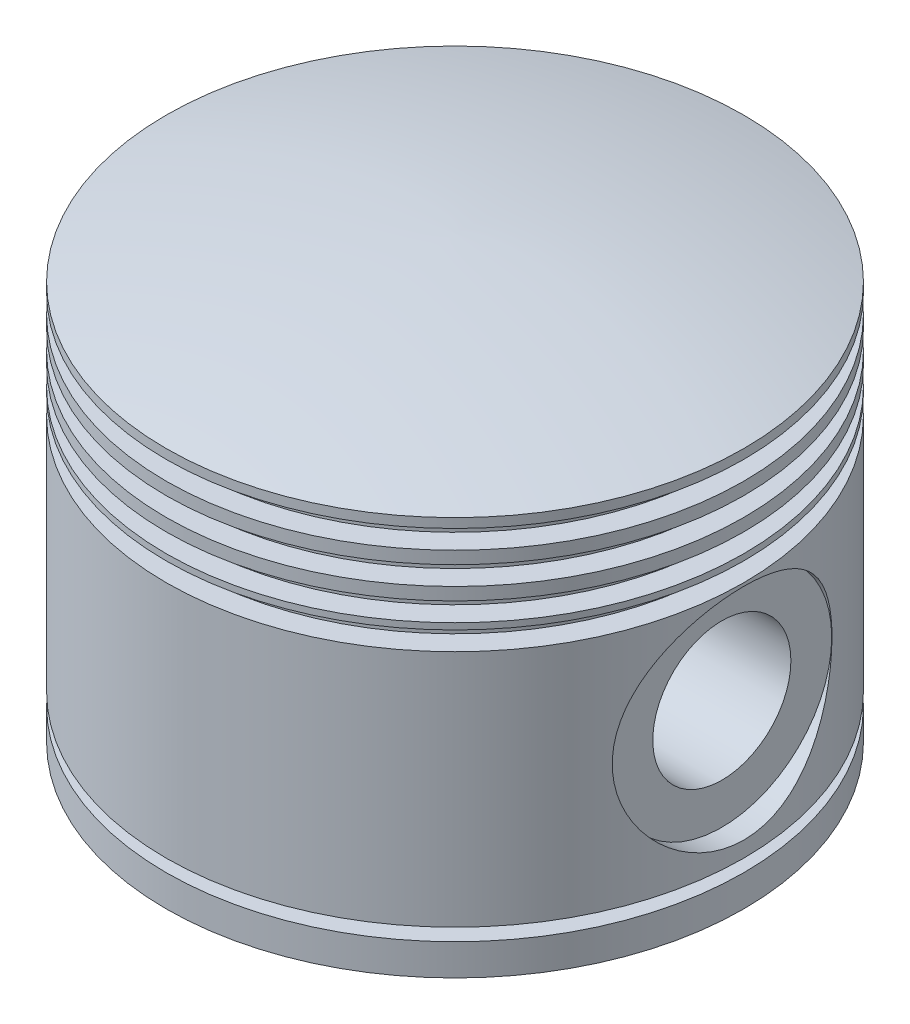
SolidWorks part; units mm, degrees
ref_plane "Front Plane" through (0, 0, 0) normal (0, 0, 1) x (1, 0, 0)
ref_plane "Top Plane" through (0, 0, 0) normal (0, 1, 0) x (1, 0, 0)
ref_plane "Right Plane" through (0, 0, 0) normal (1, 0, 0) x (0, 0, -1)
sketch "Sketch1" plane through (0, 0, 0) normal (0, 0, 1) x (1, 0, 0)
  line L0 (0, 0) -> (0, 70.18) construction
  line L1 (0, 0) -> (-46, 0) construction
  line L2 (-46, 63.5) -> (-46, 62)
  line L3 (-46, 62) -> (-42.5, 62)
  line L4 (-42.5, 62) -> (-42.5, 59)
  line L5 (-42.5, 59) -> (-46, 59)
  line L6 (-46, 59) -> (-46, 57)
  line L7 (-46, 57) -> (-42.5, 57)
  line L8 (-42.5, 57) -> (-42.5, 54)
  line L9 (-42.5, 54) -> (-46, 54)
  line L10 (-46, 54) -> (-46, 52)
  line L11 (-46, 52) -> (-42.5, 52)
  line L12 (-42.5, 52) -> (-42.5, 49)
  line L13 (-42.5, 49) -> (-46, 49)
  line L14 (-46, 49) -> (-46, 48)
  line L15 (-46, 48) -> (-42.5, 48)
  line L16 (-42.5, 48) -> (-42.5, 45)
  line L17 (-42.5, 45) -> (-46, 45)
  line L18 (-46, 45) -> (-46, 7)
  line L19 (-46, 7) -> (-42.5, 7)
  line L20 (-42.5, 7) -> (-42.5, 5)
  line L21 (-42.5, 5) -> (-46, 5)
  line L22 (-46, 5) -> (-46, 0)
  line L23 (0, 70.18) -> (0, 62)
  line L26 (-37, 0) -> (-46, 0)
  line L27 (0, 62) -> (-37, 62)
  line L28 (-37, 62) -> (-37, 0)
  arc A0 (0, 70.18) -> (-46, 63.5) centre (3.9551, -118.7786) ccw
  point P23 (-44.25, 45)
  dimension "D1" = 62
  dimension "D10" = 37
  dimension "D11" = 189
  dimension "D2" = 46
  dimension "D3" = 1.5
  dimension "D4" = 3
  dimension "D5" = 2
  dimension "D6" = 42.5
  dimension "D7" = 2
  dimension "D8" = 7
  dimension "D9" = 45
  dimension "D12" = 70.18
revolve "Revolve1" add sketch "Sketch1" angle 360 about L0
sketch "Sketch2" plane through (0, 0, 0) normal (1, 0, 0) x (0, 0, -1)
  circle A0 centre (0, 27) radius 11
  dimension "D2" = 22
  dimension "D1" = 27
extrude "Cut-Extrude1" cut sketch "Sketch2" against normal through all both and the other way through all
sketch "Sketch3" plane through (0, 0, 0) normal (1, 0, 0) x (0, 0, -1)
  circle A0 centre (0, 27) radius 17.5
  dimension "D1" = 35
extrude "Cut-Extrude6" cut sketch "Sketch3" against normal blind 3.5 from offset 46
mirror "Mirror1" about plane through (0, 0, 0) normal (1, 0, 0) of "Cut-Extrude6"
sketch "Sketch4" plane through (0, 0, 0) normal (1, 0, 0) x (0, 0, -1)
  circle A0 centre (0, 27) radius 18
  circle A1 centre (0, 27) radius 11
  circle A2 centre (0, 27) radius 11 construction
  dimension "D1" = 36
extrude "Boss-Extrude1" add sketch "Sketch4" against normal up to surface (7.3265 mm away) from offset 25 offset against normal yes
mirror "Mirror2" about plane through (0, 0, 0) normal (1, 0, 0) of "Boss-Extrude1"
sketch "Sketch6" plane through (0, 0, 0) normal (0, 0, 1) x (1, 0, 0)
  line L0 (-42.5, 27) -> (42.5, 27) construction
  line L1 (-42.5, 44.5) -> (-42.5, 9.5) construction
  line L2 (42.5, 9.5) -> (42.5, 44.5) construction
sketch "Sketch7" plane through (0, 0, 0) normal (1, 0, 0) x (0, 0, -1)
  line L0 (0, 70.18) -> (0, 0) construction
